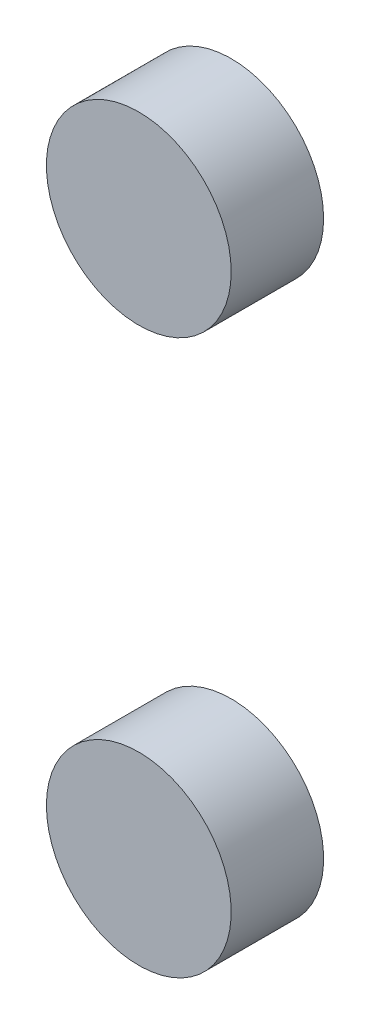
SolidWorks part; units mm, degrees
ref_plane "Front Plane" through (0, 0, 0) normal (0, 0, 1) x (1, 0, 0)
ref_plane "Top Plane" through (0, 0, 0) normal (0, 1, 0) x (1, 0, 0)
ref_plane "Right Plane" through (0, 0, 0) normal (1, 0, 0) x (0, 0, -1)
sketch "Sketch1" plane through (0, 0, 0) normal (0, 0, 1) x (1, 0, 0)
  circle A0 centre (0, 6) radius 2
  circle A1 centre (0, -6) radius 2
extrude "Boss-Extrude1" add sketch "Sketch1" along normal blind 2
